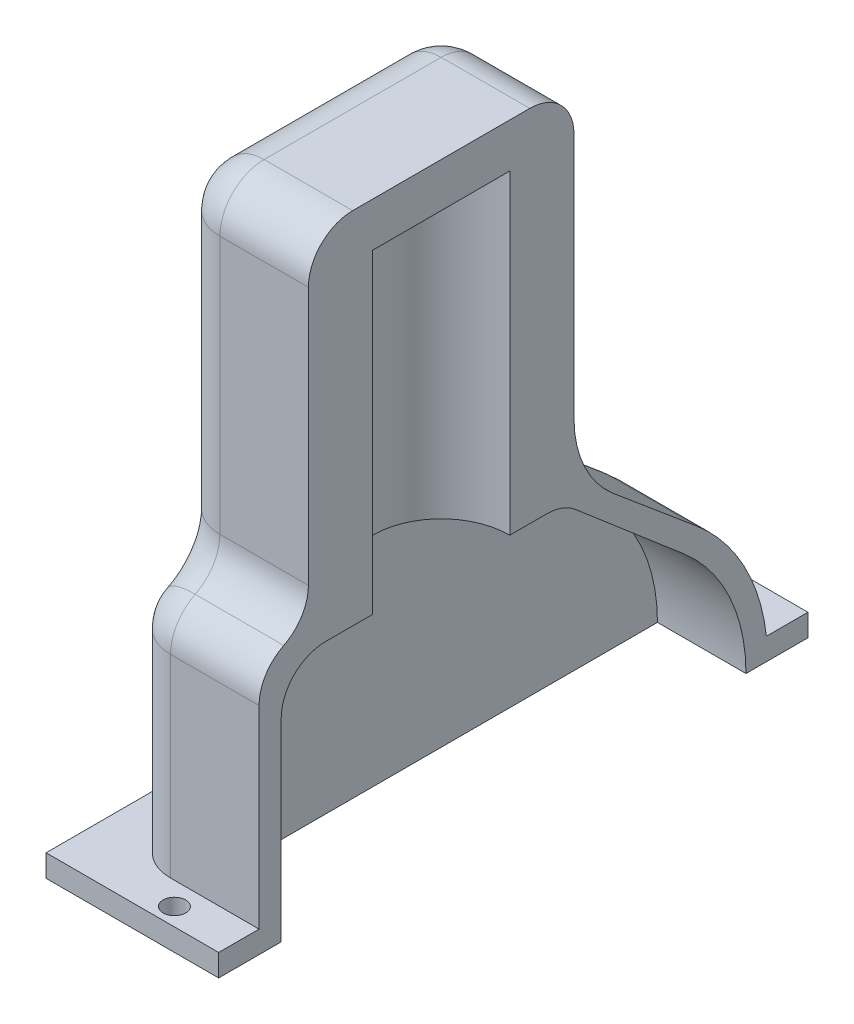
SolidWorks part; units mm, degrees
ref_plane "Front Plane" through (0, 0, 0) normal (0, 0, 1) x (1, 0, 0)
ref_plane "Top Plane" through (0, 0, 0) normal (0, 1, 0) x (1, 0, 0)
ref_plane "Right Plane" through (0, 0, 0) normal (1, 0, 0) x (0, 0, -1)
sketch "Sketch1" plane through (0, 0, 0) normal (1, 0, 0) x (0, 0, -1)
  line L0 (0, 0) -> (0, 10)
  line L1 (0, 10) -> (18, 10)
  line L2 (18, 10) -> (18, 97.5)
  line L3 (37.7691, 117.5) -> (40.2923, 117.5)
  line L4 (40.2923, 133.3669) -> (40.2923, 250)
  line L5 (60.2923, 270) -> (140.2923, 270)
  line L9 (266, 10) -> (266, 0)
  line L10 (266, 0) -> (147.7737, 0)
  line L11 (28, 0) -> (28, 87.5)
  line L12 (48, 107.5) -> (69.2923, 107.5)
  line L13 (69.2923, 107.5) -> (69.2923, 240)
  line L14 (79.2923, 250) -> (121.2923, 250)
  line L15 (131.2923, 240) -> (131.2923, 107.5)
  line L16 (131.2923, 107.5) -> (146.8387, 107.5)
  line L17 (128, 3) -> (128, 0) construction
  line L18 (100.2923, 270) -> (100.2923, 101.4493) construction
  line L19 (106.7385, 3) -> (147.1941, 3) construction
  line L20 (108.2263, 0) -> (0, 0)
  line L21 (157.7737, 0) -> (157.7737, -13.9936) construction
  line L22 (159.6945, 102.8209) -> (209.1967, 61.2836)
  line L23 (160.2923, 250) -> (160.2923, 138.6887)
  line L24 (178.1529, 100.3865) -> (215.6246, 68.944)
  line L25 (196.8887, 84.6653) -> (190.4609, 77.0048) construction
  line L26 (239.3414, 38.0356) -> (230.2783, 33.8095) construction
  line L27 (266, 10) -> (247.2164, 10)
  line L28 (69.2923, 107.5) -> (131.2923, 107.5)
  arc A0 (18, 97.5) -> (29.1461, 115.4335) centre (38, 97.5) cw
  arc A1 (29.1461, 115.4335) -> (40.2923, 133.3669) centre (20.2923, 133.3669) ccw
  arc A2 (28, 87.5) -> (48, 107.5) centre (48, 87.5) cw
  arc A3 (147.7737, 0) -> (108.2263, 0) centre (128, 3) ccw
  arc A4 (237.7737, 0) -> (209.1967, 61.2836) centre (157.7737, 0) ccw
  arc A5 (159.6945, 102.8209) -> (146.8387, 107.5) centre (146.8387, 87.5) ccw
  arc A6 (247.2164, 10) -> (215.6246, 68.944) centre (157.7737, 0) ccw
  arc A7 (178.1529, 100.3865) -> (160.2923, 138.6887) centre (210.2923, 138.6887) cw
  arc A8 (121.2923, 250) -> (131.2923, 240) centre (121.2923, 240) cw
  arc A9 (69.2923, 240) -> (79.2923, 250) centre (79.2923, 240) cw
  arc A10 (160.2923, 250) -> (140.2923, 270) centre (140.2923, 250) ccw
  arc A11 (40.2923, 250) -> (60.2923, 270) centre (60.2923, 250) cw
  point P49 (131.2923, 250)
  point P52 (69.2923, 250)
  point P55 (160.2923, 270)
  point P58 (40.2923, 270)
  dimension "D13" = 20
  dimension "D14" = 20
  dimension "D15" = 20
  dimension "D17" = 40
  dimension "D19" = 160
  dimension "D20" = 20
  dimension "D22" = 180
  dimension "D23" = 50
  dimension "D26" = 10
  dimension "D27" = 20
  dimension "D1" = 10
  dimension "D2" = 107.5
  dimension "D3" = 117.5
  dimension "D4" = 152.5
  dimension "D5" = 142.5
  dimension "D6" = 18
  dimension "D7" = 62
  dimension "D8" = 31
  dimension "D9" = 266
  dimension "D10" = 138
  dimension "D11" = 120
  dimension "D12" = 10
  dimension "D16" = 3
  dimension "D18" = 10
  dimension "D21" = 40
  dimension "D24" = 10
  dimension "D25" = 10
  dimension "D28" = 15.5465
extrude "Boss-Extrude1" add sketch "Sketch1" along normal blind 120
fillet "Fillet1" radius 20 11 edges at (120, 42.5153, -237.0987) (120, 84.6653, -196.8887) (120, 117.5578, -164.9769) (120, 194.3444, -160.2923) (120, 264.1421, -154.4344) (120, 270, -100.2923) (120, 264.1421, -46.1501) (120, 191.6835, -40.2923) (120, 122.8094, -37.2787) (120, 108.0575, -21.0136) (120, 53.75, -18)
fillet "Fillet2" radius 20 11 edges at (0, 53.75, -18) (0, 108.0575, -21.0136) (0, 122.8094, -37.2787) (0, 191.6835, -40.2923) (0, 264.1421, -46.1501) (0, 270, -100.2923) (0, 264.1421, -154.4344) (0, 194.3444, -160.2923) (0, 117.5578, -164.9769) (0, 84.6653, -196.8887) (0, 42.5153, -237.0987)
sketch "Sketch2" plane through (0, 10, 0) normal (0, 1, 0) x (1, 0, 0)
  line L1 (138, -0.25) -> (138, 93.5)
  line L2 (138, 93.5) -> (120, 93.5)
  line L3 (120, 140.2923) -> (120, 60.2923) construction
  line L9 (138, 163) -> (120, 163)
  line L10 (0, 266) -> (0, 0)
  line L11 (120, 202.7689) -> (120, 165.2971) construction
  line L12 (120, 93.5) -> (120, 0)
  line L13 (120, 163) -> (120, 266)
  line L14 (-17.9983, -0.25) -> (-17.9983, 266)
  line L15 (-17.9983, -0.25) -> (138, -0.25)
  line L16 (120, 108.2263) -> (120, 93.5)
  line L17 (120, 147.7737) -> (120, 163)
  line L18 (-17.9983, 266) -> (0, 265.9712)
  line L19 (0, 266) -> (120, 266)
  line L20 (120, 266) -> (138, 266)
  line L21 (138, 266) -> (138, 163)
  dimension "D1" = 18
  dimension "D2" = 103
  dimension "D3" = 69.5
extrude "Boss-Extrude2" add sketch "Sketch2" against normal blind 10
hole_wizard "Ø1.0mm Dowel Hole1" positions "Sketch3" profile "Sketch4" hole size "Ø1.0" standard "ISO" end condition through all
sketch "Sketch3" plane through (0, 10, 0) normal (0, 1, 0) x (1, 0, 0)
  line L0 (-17.9983, -0.25) -> (-17.9983, 266) construction
  line L1 (138, 266) -> (0, 266) construction
  point P0 (32.0017, 258)
  point P2 (82.0017, 258)
  dimension "D1" = 50
  dimension "D2" = 50
  dimension "D3" = 8
sketch "Sketch4" plane through (32.0017, 10, -258) normal (1, 0, 0) x (0, 0, 1)
  line L0 (0, 0) -> (0, 10)
  line L1 (0, 10) -> (5.1, 10)
  line L2 (5.1, 10) -> (5.1, 0)
  line L5 (5.1, 0) -> (0, 0)
  line L11 (0, -6.35) -> (0, 107.95) construction
  dimension "Thru Hole Dia." = 10.2
  dimension "Thru Hole Depth" = 10
hole_wizard "Ø1.0mm Dowel Hole2" positions "Sketch5" profile "Sketch6" hole size "Ø1.0" standard "ISO" end condition through all
sketch "Sketch5" plane through (0, 10, 0) normal (0, 1, 0) x (1, 0, 0)
  line L0 (-17.9983, -0.25) -> (-17.9983, 266) construction
  line L1 (-17.9983, -0.25) -> (138, -0.25) construction
  line L2 (138, -0.25) -> (138, 93.5) construction
  line L3 (138, 266) -> (138, 163) construction
  point P0 (-9.9983, 205.75)
  point P2 (-9.9983, 135.75)
  point P4 (-9.9983, 65.75)
  point P6 (32.0017, 7.75)
  point P8 (82.0017, 7.75)
  point P10 (130, 65.75)
  point P12 (130, 205.75)
  dimension "D1" = 70
  dimension "D2" = 70
  dimension "D3" = 8
  dimension "D4" = 66
  dimension "D5" = 50
  dimension "D6" = 50
  dimension "D7" = 8
  dimension "D8" = 8
  dimension "D9" = 8
  dimension "D10" = 140
  dimension "D11" = 66
sketch "Sketch6" plane through (-9.9983, 10, -205.75) normal (1, 0, 0) x (0, 0, 1)
  line L0 (0, 0) -> (0, 10)
  line L1 (0, 10) -> (5.1, 10)
  line L2 (5.1, 10) -> (5.1, 0)
  line L5 (5.1, 0) -> (0, 0)
  line L11 (0, -6.35) -> (0, 107.95) construction
  dimension "Thru Hole Dia." = 10.2
  dimension "Thru Hole Depth" = 10
sketch "Sketch7" plane through (0, 0, 0) normal (0, -1, 0) x (1, 0, 0)
  line L0 (-17.9983, 0.25) -> (138, 0.25) construction
  line L1 (-17.9983, 0.25) -> (-17.9983, -266) construction
  circle A0 centre (60.0017, -100.29) radius 31
  dimension "D1" = 62
  dimension "D2" = 100.54
  dimension "D3" = 78
extrude "Cut-Extrude1" cut sketch "Sketch7" against normal blind 250
ref_plane "Plane1" through (60, 0, 0) normal (1, 0, 0) x (0, 0, -1)
sketch "Sketch9" plane through (60, 0, 0) normal (1, 0, 0) x (0, 0, -1)
  line L0 (0, 0) -> (28, 0)
  line L1 (-0.25, 0) -> (93.5, 0) construction
  line L2 (28, 0) -> (28, 87.5)
  line L3 (48, 107.5) -> (148, 107.5)
  line L4 (160.9986, 102.6998) -> (209.9946, 60.7994)
  line L5 (155.3856, 107.5) -> (165.3856, 107.5)
  line L6 (158, 0) -> (147.7737, 0)
  line L7 (28, 0) -> (108.2263, 0)
  line L8 (158, 0) -> (238, 0)
  line L9 (108.2263, 0) -> (28, 0)
  line L10 (158, 29.7733) -> (158, -25.4759) construction
  arc A0 (147.7737, 0) -> (108.2263, 0) centre (128, 3) ccw
  arc A1 (28, 87.5) -> (48, 107.5) centre (48, 87.5) cw
  arc A2 (238, 0) -> (209.9946, 60.7994) centre (158, 0) ccw
  arc A3 (160.9986, 102.6998) -> (148, 107.5) centre (148, 87.5) ccw
  point P19 (28, 107.5)
  dimension "D3" = 20
  dimension "D5" = 160
  dimension "D8" = 20
  dimension "D1" = 28
  dimension "D2" = 107.5
  dimension "D4" = 30
  dimension "D6" = 10
  dimension "D7" = 100
extrude "Cut-Extrude2" cut sketch "Sketch9" along normal mid plane 80
sketch "Sketch10" plane through (20, 0, 0) normal (1, 0, 0) x (0, 0, -1)
  line L0 (28, 0) -> (238, 0)
  line L1 (107.1779, 3) -> (155.5793, 3) construction
  arc A0 (147.7737, 0) -> (108.2263, 0) centre (128, 3) ccw
  arc M3 (108.2263, 0) -> (147.7737, 0) centre (128, 3) cw
  dimension "D1" = 3
extrude "Boss-Extrude3" add sketch "Sketch10" against normal blind 20 contours A0 L1 | L1 L0 M3
ref_plane "Plane2" through (138, 0, 0) normal (1, 0, 0) x (0, 0, -1)
sketch "Sketch12" plane through (138, 0, 0) normal (1, 0, 0) x (0, 0, -1)
  line L1 (-45.259, 282.6371) -> (312.5991, 282.6371)
  line L2 (-45.259, 282.6371) -> (-45.259, -37.4155)
  line L3 (-45.259, -37.4155) -> (312.5991, -37.4155)
  line L4 (312.5991, 282.6371) -> (312.5991, -37.4155)
extrude "Cut-Extrude3" cut sketch "Sketch12" against normal blind 78
